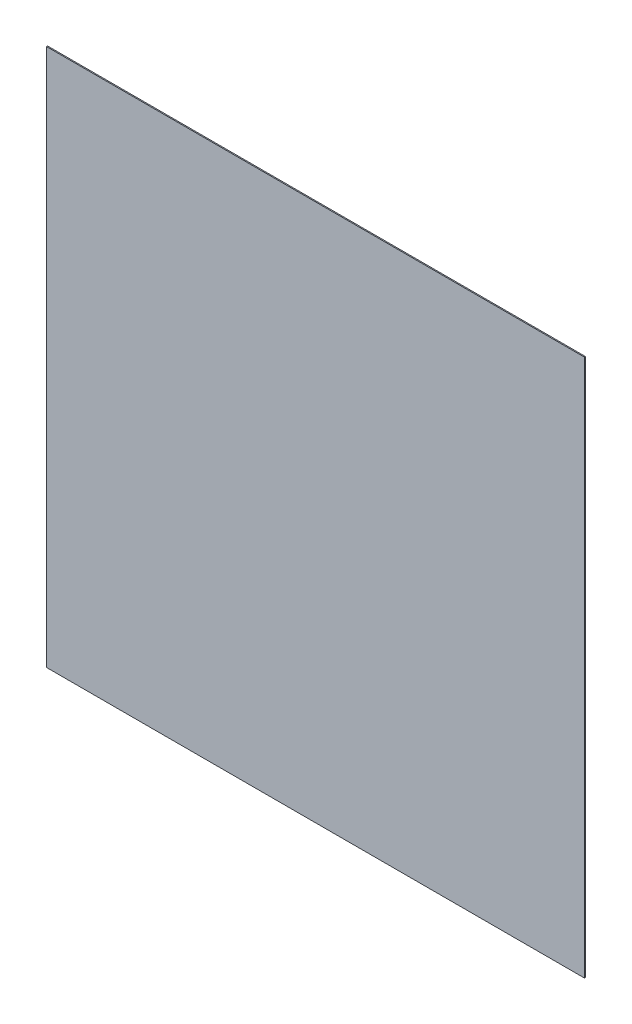
SolidWorks part; units mm, degrees
ref_plane "Front Plane" through (0, 0, 0) normal (0, 0, 1) x (1, 0, 0)
ref_plane "Top Plane" through (0, 0, 0) normal (0, 1, 0) x (1, 0, 0)
ref_plane "Right Plane" through (0, 0, 0) normal (1, 0, 0) x (0, 0, -1)
sketch "Sketch1" plane through (0, 0, 0) normal (0, 0, 1) x (1, 0, 0)
  line L1 (1252, -1252) -> (-1252, -1252)
  line L2 (1252, -1252) -> (1252, 1252)
  line L3 (1252, 1252) -> (-1252, 1252)
  line L4 (-1252, -1252) -> (-1252, 1252)
  line L5 (1252, -1252) -> (-1252, 1252) construction
  line L6 (1252, 1252) -> (-1252, -1252) construction
  point P0 (0, 0)
  dimension "D1" = 2504
  dimension "D2" = 2504
extrude "Boss-Extrude1" add sketch "Sketch1" along normal blind 5
